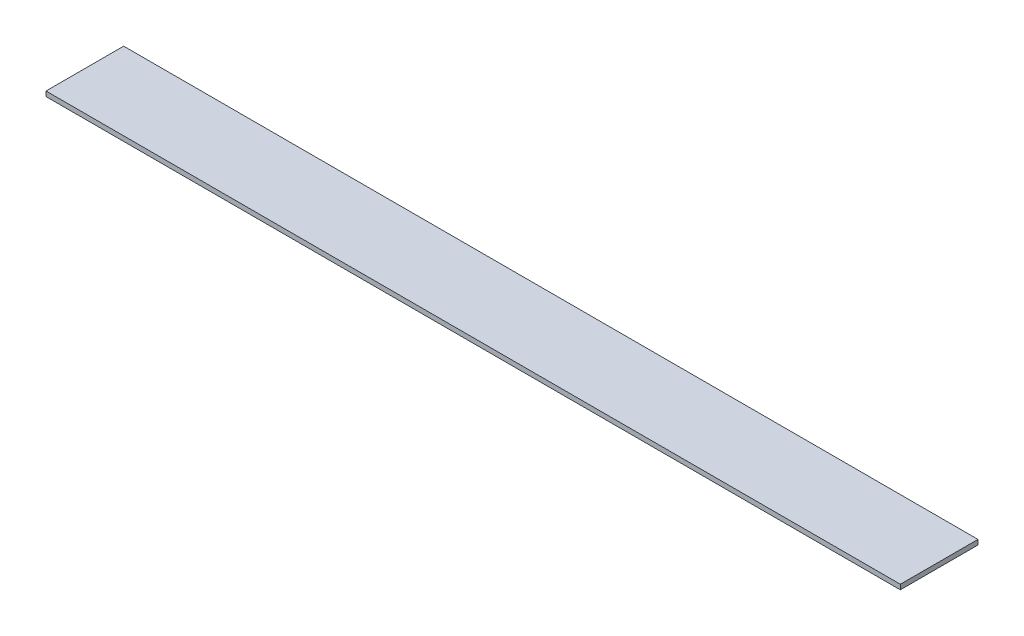
SolidWorks part; units mm, degrees
ref_plane "Front Plane" through (0, 0, 0) normal (0, 0, 1) x (1, 0, 0)
ref_plane "Top Plane" through (0, 0, 0) normal (0, 1, 0) x (1, 0, 0)
ref_plane "Right Plane" through (0, 0, 0) normal (1, 0, 0) x (0, 0, -1)
sketch "Sketch1" plane through (0, 0, 0) normal (0, 1, 0) x (1, 0, 0)
  line L1 (-139.7, -12.7) -> (139.7, -12.7)
  line L2 (-139.7, -12.7) -> (-139.7, 12.7)
  line L3 (-139.7, 12.7) -> (139.7, 12.7)
  line L4 (139.7, -12.7) -> (139.7, 12.7)
  line L5 (-139.7, -12.7) -> (139.7, 12.7) construction
  line L6 (-139.7, 12.7) -> (139.7, -12.7) construction
  point P0 (0, 0)
  dimension "D1" = 279.4
  dimension "D2" = 25.4
extrude "Boss-Extrude1" add sketch "Sketch1" along normal mid plane 1.5875
